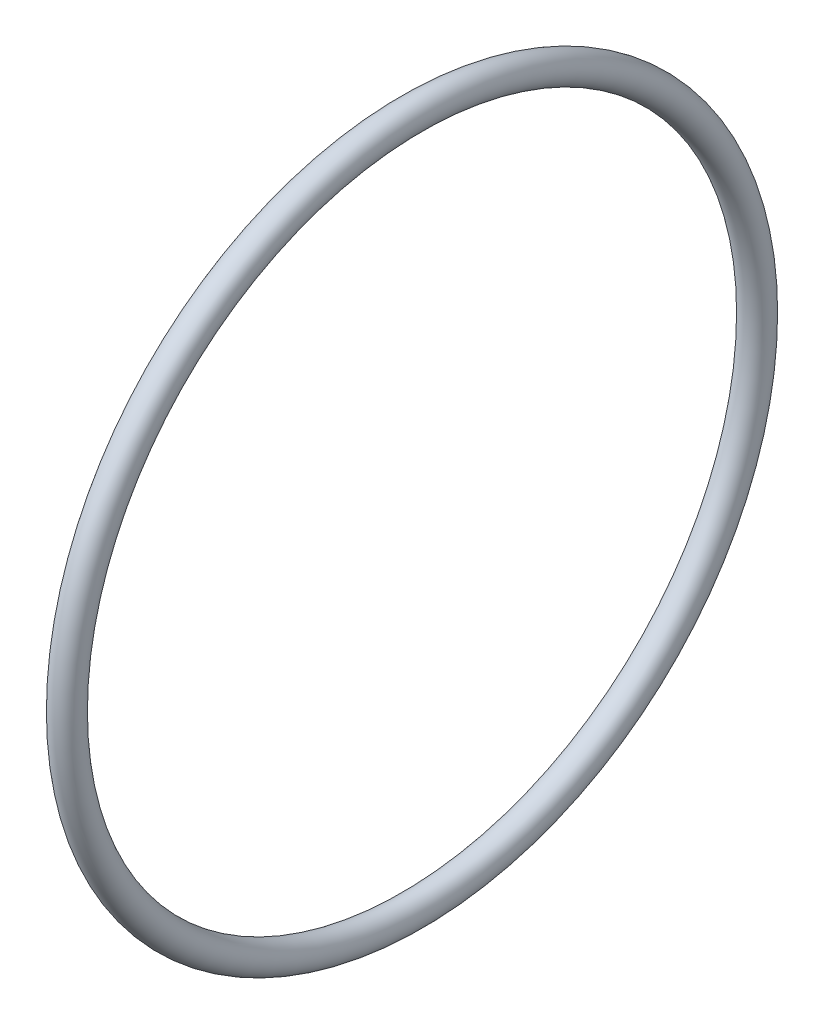
SolidWorks part; units mm, degrees
ref_plane "Front Plane" through (0, 0, 0) normal (0, 0, 1) x (1, 0, 0)
ref_plane "Top Plane" through (0, 0, 0) normal (0, 1, 0) x (1, 0, 0)
ref_plane "Right Plane" through (0, 0, 0) normal (1, 0, 0) x (0, 0, -1)
sketch "Sketch6" plane through (0, 0, 0) normal (0, 1, 0) x (1, 0, 0)
  line L0 (-88.898, 0) -> (91.9658, 0) construction
sketch "Sketch4" plane through (0, 0, 0) normal (0, 0, 1) x (1, 0, 0)
  circle A0 centre (0, 21.4) radius 0.9
  dimension "D1" = 1.8
  dimension "D2" = 21.4
revolve "Revolve1" add sketch "Sketch4" angle 360 about L0
sketch "Sketch7" plane through (0, 0, 0) normal (1, 0, 0) x (0, 0, -1)
  circle A0 centre (0, 0.2854) radius 18 construction
  dimension "D1" = 36
